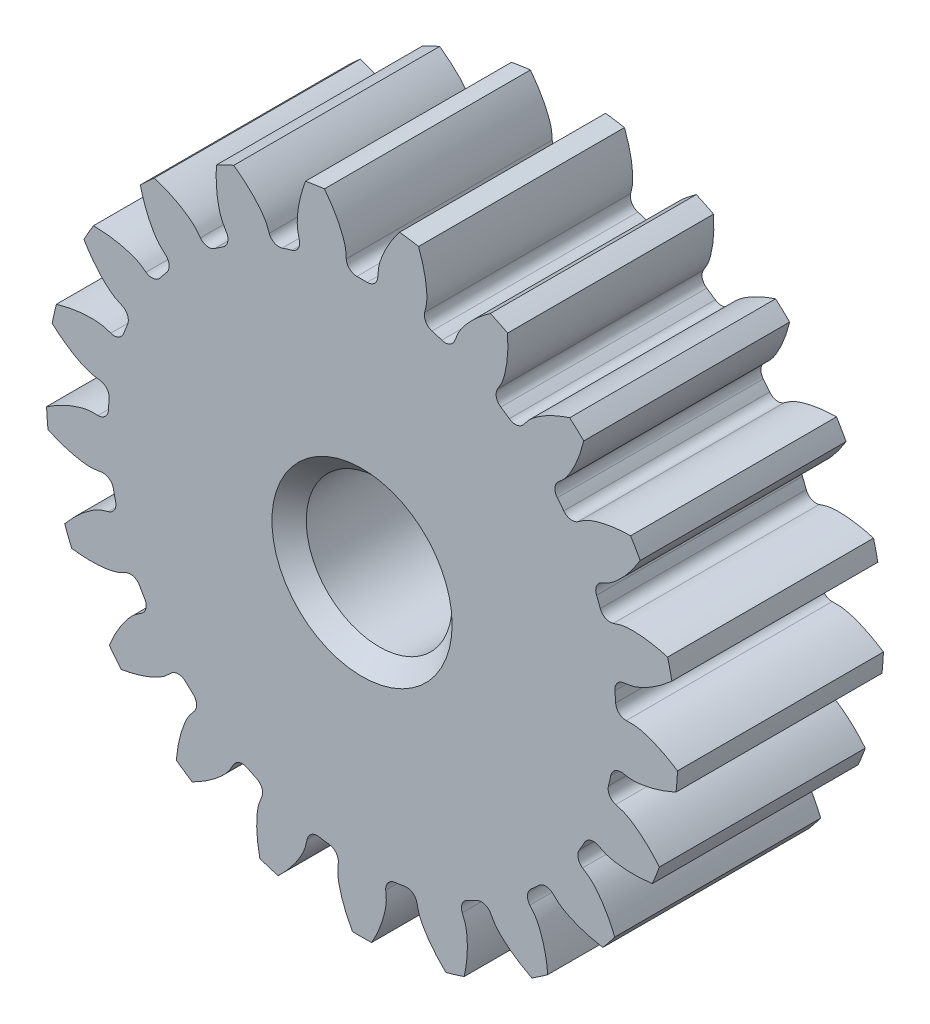
SolidWorks part; units mm, degrees
ref_plane "Front Plane" through (0, 0, 0) normal (0, 0, 1) x (1, 0, 0)
ref_plane "Top Plane" through (0, 0, 0) normal (0, 1, 0) x (1, 0, 0)
ref_plane "Right Plane" through (0, 0, 0) normal (1, 0, 0) x (0, 0, -1)
ref_axis "Axis1" through (0, 0, -88.99) along (0, 0, 1)
sketch "Sketch1" plane through (0, 0, 0) normal (0, 0, 1) x (1, 0, 0)
  circle A0 centre (0, 0) radius 9.2
extrude "LaShenA" add sketch "Sketch1" along normal blind 6
sketch "SketchA" plane through (0, 0, 6) normal (0, 0, 1) x (1, 0, 0)
  line L0 (0, 0) -> (0, 9.2) construction
  arc A0 (0.1502, 7.3985) -> (-0.1502, 7.3985) centre (0, 0) ccw
  arc A1 (1.4402, 9.5361) -> (-1.4402, 9.5361) centre (0, 0) ccw
  arc A2 (-0.1502, 7.3985) -> (-0.4598, 7.6841) centre (-0.1563, 7.7024) cw
  arc A3 (0.4598, 7.6841) -> (0.1502, 7.3985) centre (0.1563, 7.7024) cw
  circle A4 centre (0, 0) radius 7.8934 construction
  circle A5 centre (0, 0) radius 9.2 construction
  circle A6 centre (0, 0) radius 7.4 construction
  circle A7 centre (0, 0) radius 8.4 construction
  spline S0 degree 3 poles (0.4598, 7.6841) (0.4637, 7.7496) (0.4664, 7.8384) (0.4807, 7.9372) (0.4906, 7.9832) (0.4994, 8.0195) (0.5106, 8.0612) (0.5246, 8.1081) (0.5417, 8.16) (0.5621, 8.2169) (0.5861, 8.2786) (0.6139, 8.3449) (0.646, 8.4157) (0.6824, 8.4908) (0.7235, 8.5699) (0.7695, 8.653) (0.8207, 8.7397) (0.8772, 8.8299) (0.9394, 8.9234) (1.0073, 9.0198) (1.0813, 9.119) (1.1615, 9.2207) (1.2793, 9.3622) (1.374, 9.4667) (1.4402, 9.5361) knots 0.123319 0.123319 0.123319 0.123319 0.203409 0.232856 0.245818 0.261137 0.278814 0.298847 0.321236 0.345983 0.373086 0.402547 0.434364 0.468537 0.505068 0.543956 0.5852 0.628801 0.674759 0.723074 0.773745 0.826774 0.882159 1 1 1 1
  spline S1 degree 3 poles (-0.4598, 7.6841) (-0.4637, 7.7496) (-0.4664, 7.8384) (-0.4807, 7.9372) (-0.4906, 7.9832) (-0.4994, 8.0195) (-0.5106, 8.0612) (-0.5246, 8.1081) (-0.5417, 8.16) (-0.5621, 8.2169) (-0.5861, 8.2786) (-0.6139, 8.3449) (-0.646, 8.4157) (-0.6824, 8.4908) (-0.7235, 8.5699) (-0.7695, 8.653) (-0.8207, 8.7397) (-0.8772, 8.8299) (-0.9394, 8.9234) (-1.0073, 9.0198) (-1.0813, 9.119) (-1.1615, 9.2207) (-1.2793, 9.3622) (-1.374, 9.4667) (-1.4402, 9.5361) knots 0.123319 0.123319 0.123319 0.123319 0.203409 0.232856 0.245818 0.261137 0.278814 0.298847 0.321236 0.345983 0.373086 0.402547 0.434364 0.468537 0.505068 0.543956 0.5852 0.628801 0.674759 0.723074 0.773745 0.826774 0.882159 1 1 1 1
  dimension "D1" = 0.304
  dimension "Db" = 15.7868
  dimension "Da" = 18.4
  dimension "Df" = 14.8
  dimension "Dn" = 16.8
extrude "Cut-ExtrudeA" cut sketch "SketchA" against normal blind 6
pattern_circular "www.KYTool.cn" count 21 over 360 about axis through (0, 0, -88.99) along (0, 0, 1) of "Cut-ExtrudeA"
sketch "Sketch3" plane through (0, 0, 6) normal (0, 0, 1) x (1, 0, 0)
  circle A0 centre (0, 0) radius 2.125
  dimension "D1" = 4.25
extrude "Cut-Extrude2" cut sketch "Sketch3" against normal through all
chamfer "Chamfer1" distance 0.5 angle 45 2 edges at (2.125, 0, 6) (2.125, 0, 0)
